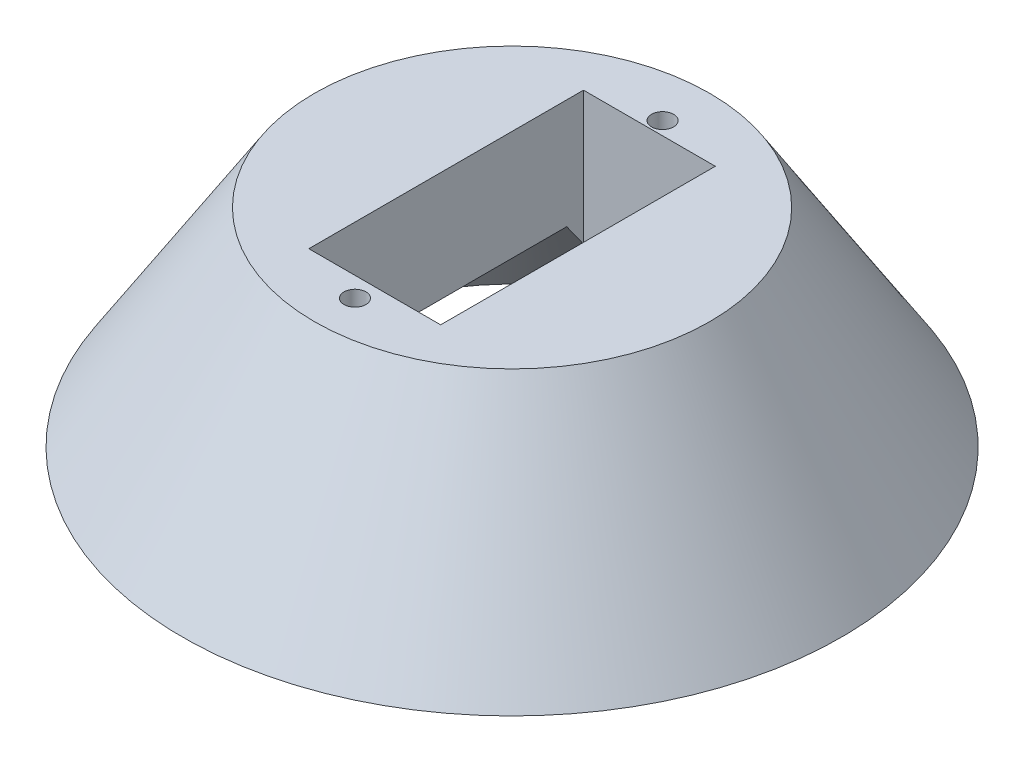
SolidWorks part; units mm, degrees
material "Pure Gold"
ref_plane "Front Plane" through (0, 0, 0) normal (0, 0, 1) x (1, 0, 0)
ref_plane "Top Plane" through (0, 0, 0) normal (0, 1, 0) x (1, 0, 0)
ref_plane "Right Plane" through (0, 0, 0) normal (1, 0, 0) x (0, 0, -1)
sketch "Sketch5" plane through (0, 0, 0) normal (0, 0, 1) x (1, 0, 0)
  line L0 (0, 0) -> (0, 18.8727)
  line L1 (0, 18.8727) -> (-18, 18.8727)
  line L2 (-18, 18.8727) -> (-30, 0)
  line L3 (-30, 0) -> (0, 0)
revolve "Revolve3" add sketch "Sketch5" angle 360 about L0
sketch "Sketch6" plane through (0, 18.8727, 0) normal (0, 1, 0) x (1, 0, 0)
  line L1 (-6, 12.5) -> (6, 12.5)
  line L2 (-6, 12.5) -> (-6, -12.5)
  line L3 (-6, -12.5) -> (6, -12.5)
  line L4 (6, 12.5) -> (6, -12.5)
  line L5 (-6, 12.5) -> (6, -12.5) construction
  line L6 (-6, -12.5) -> (6, 12.5) construction
  point P0 (0, 0)
  dimension "D1" = 25
  dimension "D2" = 12
shell "Shell2" thickness 10
extrude "Cut-Extrude2" cut sketch "Sketch6" against normal through all
sketch "Sketch7" plane through (0, 18.8727, 0) normal (0, 1, 0) x (1, 0, 0)
  line L0 (-6, -12.5) -> (6, -12.5) construction
  circle A0 centre (0, 13.7) radius 1
  circle A1 centre (0, -14.3) radius 1
  point P4 (0, -12.5)
  dimension "D1" = 2
  dimension "D2" = 2
  dimension "D3" = 1.8
  dimension "D4" = 1.2
extrude "Cut-Extrude3" cut sketch "Sketch7" against normal blind 5
